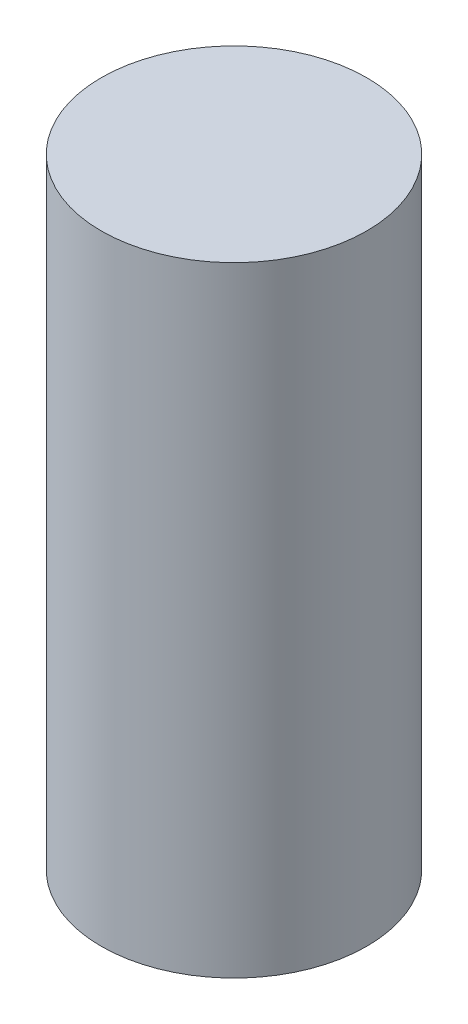
SolidWorks part; units mm, degrees
ref_plane "Front Plane" through (0, 0, 0) normal (0, 0, 1) x (1, 0, 0)
ref_plane "Top Plane" through (0, 0, 0) normal (0, 1, 0) x (1, 0, 0)
ref_plane "Right Plane" through (0, 0, 0) normal (1, 0, 0) x (0, 0, -1)
other "Configuration Table"
sketch "Sketch1" plane through (0, 0, 0) normal (0, 1, 0) x (1, 0, 0)
  circle A0 centre (650, 50) radius 6
extrude "TOPPING_ayar_mil_2" add sketch "Sketch1" along normal blind 28 from offset 12 separate body
